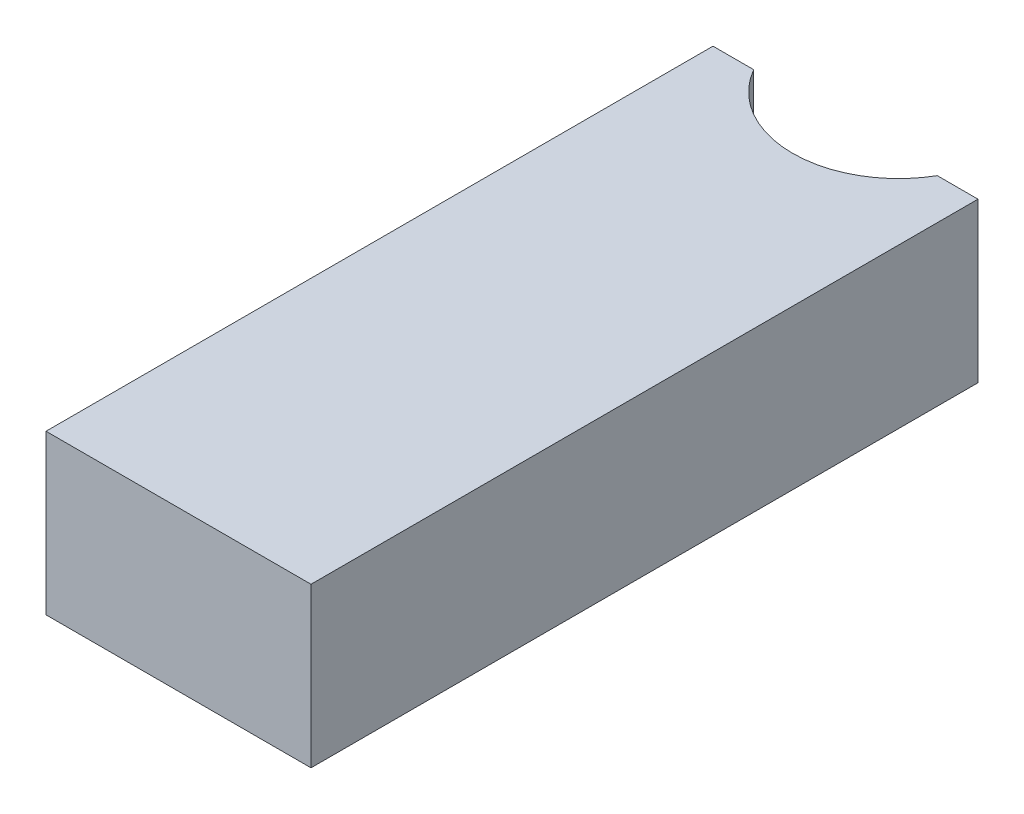
SolidWorks part; units mm, degrees
material "Custom Plastic"
ref_plane "X-Y Datum" through (0, 0, 0) normal (0, 0, 1) x (1, 0, 0)
ref_plane "X-Z Datum" through (0, 0, 0) normal (0, 1, 0) x (1, 0, 0)
ref_plane "Y-Z Datum" through (0, 0, 0) normal (1, 0, 0) x (0, 0, -1)
sketch "Sketch1" plane through (0, 0, 0) normal (0, 0, 1) x (1, 0, 0)
  line L1 (-15.875, 9.525) -> (15.875, 9.525)
  line L2 (-15.875, 9.525) -> (-15.875, -9.525)
  line L3 (-15.875, -9.525) -> (15.875, -9.525)
  line L4 (15.875, 9.525) -> (15.875, -9.525)
  line L5 (-15.875, 9.525) -> (15.875, -9.525) construction
  line L6 (-15.875, -9.525) -> (15.875, 9.525) construction
  point P0 (0, 0)
  dimension "D1" = 31.75
  dimension "D2" = 19.05
extrude "Boss-Extrude1" add sketch "Sketch1" along normal blind 79.9084
sketch "Sketch2" plane through (0, 9.525, 0) normal (0, 1, 0) x (1, 0, 0)
  circle A0 centre (0, 6.35) radius 12.7
  point P2 (0, -6.35)
  dimension "D1" = 25.4
  dimension "D2" = 6.35
extrude "Cut-Extrude1" cut sketch "Sketch2" against normal through all
